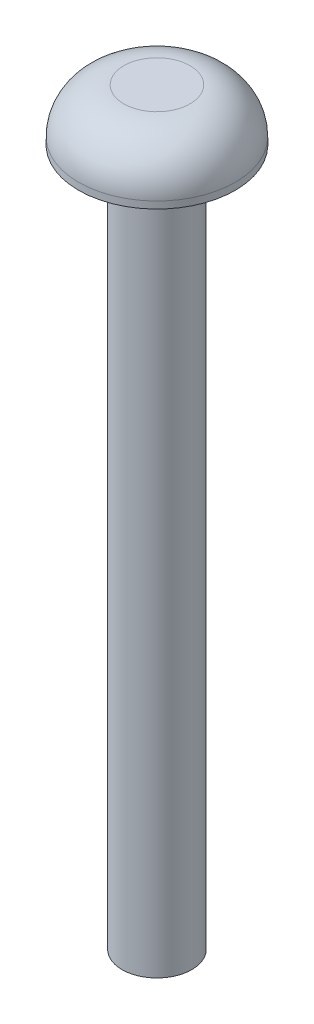
SolidWorks part; units mm, degrees
ref_plane "Front Plane" through (0, 0, 0) normal (0, 0, 1) x (1, 0, 0)
ref_plane "Top Plane" through (0, 0, 0) normal (0, 1, 0) x (1, 0, 0)
ref_plane "Right Plane" through (0, 0, 0) normal (1, 0, 0) x (0, 0, -1)
sketch "Sketch1" plane through (0, 0, 0) normal (0, 1, 0) x (1, 0, 0)
  circle A0 centre (0, 0) radius 2
  dimension "D1" = 4
extrude "Boss-Extrude1" add sketch "Sketch1" along normal blind 40
sketch "Sketch2" plane through (0, 40, 0) normal (0, 1, 0) x (1, 0, 0)
  circle A0 centre (0, 0) radius 4.5
  dimension "D1" = 9
extrude "Boss-Extrude2" add sketch "Sketch2" along normal blind 3
fillet "Fillet1" radius 2.6 1 edges at (0, 43, 4.5)
